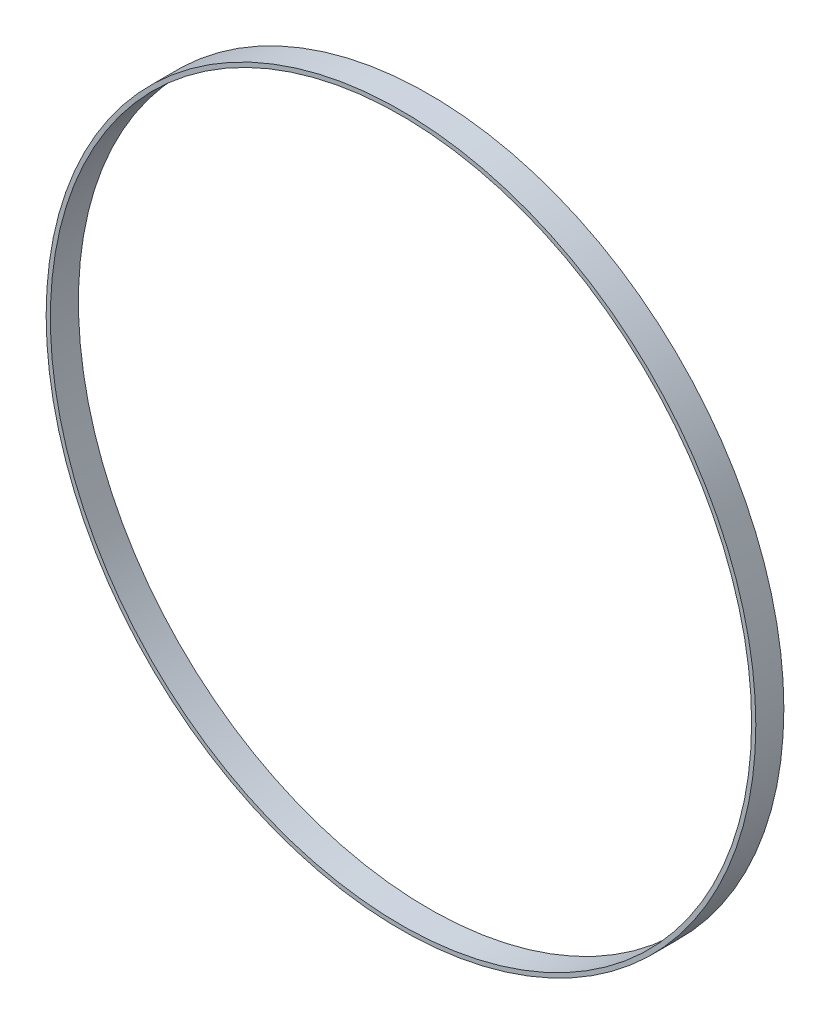
SolidWorks part; units mm, degrees
ref_plane "Front Plane" through (0, 0, 0) normal (0, 0, 1) x (1, 0, 0)
ref_plane "Top Plane" through (0, 0, 0) normal (0, 1, 0) x (1, 0, 0)
ref_plane "Right Plane" through (0, 0, 0) normal (1, 0, 0) x (0, 0, -1)
sketch "Sketch1" plane through (0, 0, 0) normal (0, 0, 1) x (1, 0, 0)
  circle A0 centre (0, 0) radius 250
  circle A1 centre (0, 0) radius 253
  dimension "D1" = 500
  dimension "D2" = 3
extrude "Boss-Extrude1" add sketch "Sketch1" along normal blind 20
